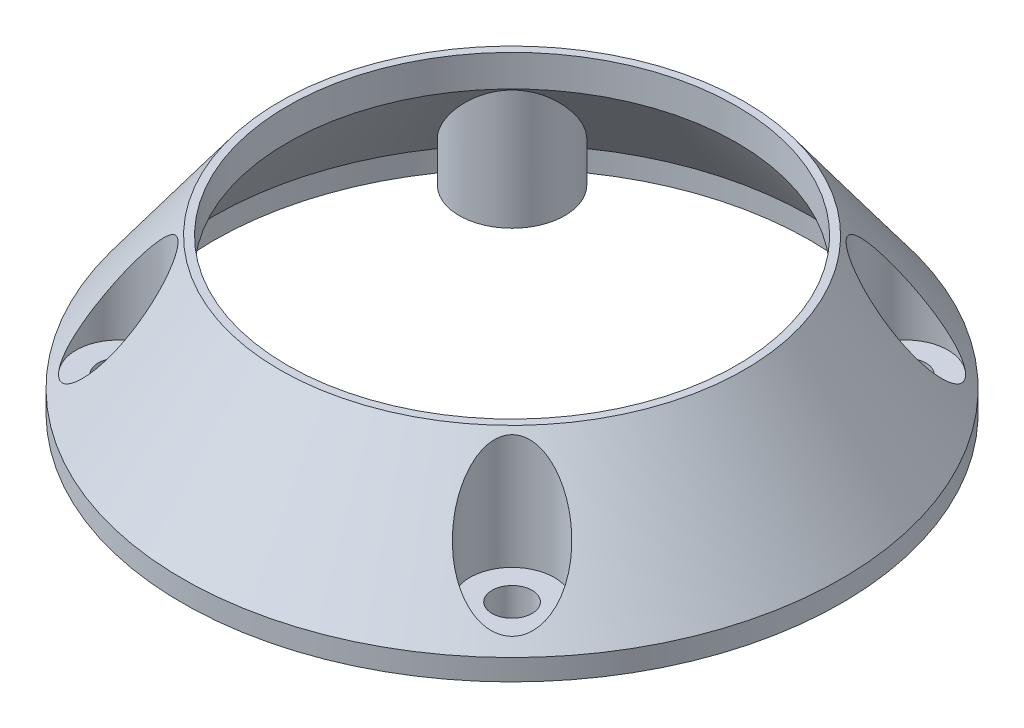
SolidWorks part; units mm, degrees
material "6061-T6 (SS)"
ref_plane "Front Plane" through (0, 0, 0) normal (0, 0, 1) x (1, 0, 0)
ref_plane "Top Plane" through (0, 0, 0) normal (0, 1, 0) x (1, 0, 0)
ref_plane "Right Plane" through (0, 0, 0) normal (1, 0, 0) x (0, 0, -1)
sketch "Sketch3" plane through (0, 0, 0) normal (0, 0, 1) x (1, 0, 0)
  line L0 (0, -74.5829) -> (0, 74.5829) construction
  line L10 (-21.1173, 0) -> (56.8383, 0) construction
  line L11 (35.89, 0) -> (27, 12.0946)
  line L12 (27, 12.0946) -> (27, 17.1746)
  line L13 (27, 17.1746) -> (39.624, 0)
  line L15 (35.89, 0) -> (35.89, -2.54)
  line L16 (35.89, -2.54) -> (39.624, -2.54)
  line L17 (39.624, -2.54) -> (39.624, 0)
  point P5 (27, 13.2372)
  point P13 (39.624, -0.1595)
  dimension "D1" = 79.248
  dimension "D2" = 54
  dimension "D3" = 2.54
  dimension "D4" = 5.08
  dimension "D5" = 8.89
revolve "Revolve1" add sketch "Sketch3" angle 360 about L0
sketch "Sketch4" plane through (0, -2.54, 0) normal (0, -1, 0) x (1, 0, 0)
  line L0 (0, -53.6346) -> (0, 53.6346) construction
  line L1 (-50.2847, 0) -> (55.027, 0) construction
  line L2 (-19.2177, 28.198) -> (-20.4876, 29.4678)
  line L7 (-23.7079, -23.7079) -> (23.7079, -23.7079) construction
  line L8 (-23.7079, -23.7079) -> (-23.7079, 23.7079) construction
  line L9 (-23.7079, 23.7079) -> (23.7079, 23.7079) construction
  line L10 (23.7079, -23.7079) -> (23.7079, 23.7079) construction
  line L11 (-23.7079, -23.7079) -> (23.7079, 23.7079) construction
  line L12 (-23.7079, 23.7079) -> (23.7079, -23.7079) construction
  line L13 (-28.198, 19.2177) -> (-29.4678, 20.4876)
  line L14 (-28.198, 19.2177) -> (-19.2177, 28.198) construction
  line L15 (28.198, 19.2177) -> (19.2177, 28.198) construction
  line L16 (28.198, 19.2177) -> (29.4678, 20.4876)
  line L17 (19.2177, 28.198) -> (20.4876, 29.4678)
  line L18 (28.198, -19.2177) -> (19.2177, -28.198) construction
  line L19 (-28.198, -19.2177) -> (-19.2177, -28.198) construction
  line L20 (-23.7079, -23.7079) -> (23.7079, -23.7079) construction
  line L21 (19.2177, -28.198) -> (20.4876, -29.4678)
  line L22 (28.198, -19.2177) -> (29.4678, -20.4876)
  line L23 (-28.198, -19.2177) -> (-29.4678, -20.4876)
  line L24 (-19.2177, -28.198) -> (-20.4876, -29.4678)
  arc A0 (-28.198, 19.2177) -> (-19.2177, 28.198) centre (-23.7079, 23.7079) ccw
  circle A1 centre (0, 0) radius 35.89 construction
  arc A5 (-20.4876, 29.4678) -> (-29.4678, 20.4876) centre (0, 0) ccw
  arc A7 (20.4876, 29.4678) -> (29.4678, 20.4876) centre (0, 0) cw
  arc A8 (28.198, 19.2177) -> (19.2177, 28.198) centre (23.7079, 23.7079) cw
  arc A9 (28.198, -19.2177) -> (19.2177, -28.198) centre (23.7079, -23.7079) ccw
  arc A10 (20.4876, -29.4678) -> (29.4678, -20.4876) centre (0, 0) ccw
  arc A11 (-20.4876, -29.4678) -> (-29.4678, -20.4876) centre (0, 0) cw
  arc A12 (-28.198, -19.2177) -> (-19.2177, -28.198) centre (-23.7079, -23.7079) cw
  point P5 (0, 0)
  point P6 (0, 0)
  point P15 (-20.4896, 29.4664)
  dimension "D2" = 12.7
  dimension "D1" = 67.056
extrude "Boss-Extrude2" add sketch "Sketch4" against normal up to surface (2.54 mm away)
sketch "Sketch6" plane through (0, -2.54, 0) normal (0, -1, 0) x (1, 0, 0)
  line L0 (0, -43.6677) -> (0, 46.4776) construction
  line L1 (-23.672, -23.672) -> (23.672, -23.672) construction
  line L2 (-23.672, -23.672) -> (-23.672, 23.672) construction
  line L3 (-23.672, 23.672) -> (23.672, 23.672) construction
  line L4 (23.672, -23.672) -> (23.672, 23.672) construction
  line L5 (-23.672, -23.672) -> (23.672, 23.672) construction
  line L6 (-23.672, 23.672) -> (23.672, -23.672) construction
  line L7 (-53.8984, 0) -> (50.6177, 0) construction
  circle A1 centre (-23.672, 23.672) radius 2.413
  circle A2 centre (23.672, 23.672) radius 2.413
  circle A3 centre (23.672, -23.672) radius 2.413
  circle A4 centre (-23.672, -23.672) radius 2.413
  point P0 (0, 0)
  dimension "D2" = 4.826
  dimension "D1" = 66.9544
extrude "Cut-Extrude3" cut sketch "Sketch6" against normal through all
ref_plane "Plane2" through (0, 17.1746, 0) normal (0, 1, 0) x (1, 0, 0)
sketch "Sketch7" plane through (0, 17.1746, 0) normal (0, 1, 0) x (1, 0, 0)
  line L0 (0, -9.7335) -> (0, 8.8523) construction
  line L1 (-21.9329, 0) -> (14.1583, 0) construction
  circle A0 centre (-23.672, 23.672) radius 5.08
  circle A1 centre (23.672, 23.672) radius 5.08
  circle A2 centre (23.672, -23.672) radius 5.08
  circle A3 centre (-23.672, -23.672) radius 5.08
  point P17 (0, 0)
  dimension "D1" = 10.16
  dimension "D2" = 4
extrude "Cut-Extrude6" cut sketch "Sketch7" along a picked direction on the side against the normal blind 15.7234
sketch "Sketch8" plane through (0, 17.1746, 0) normal (0, 1, 0) x (1, 0, 0)
  circle A0 centre (0, 0) radius 51.3183
extrude "Cut-Extrude7" cut sketch "Sketch8" against normal blind 1.27
